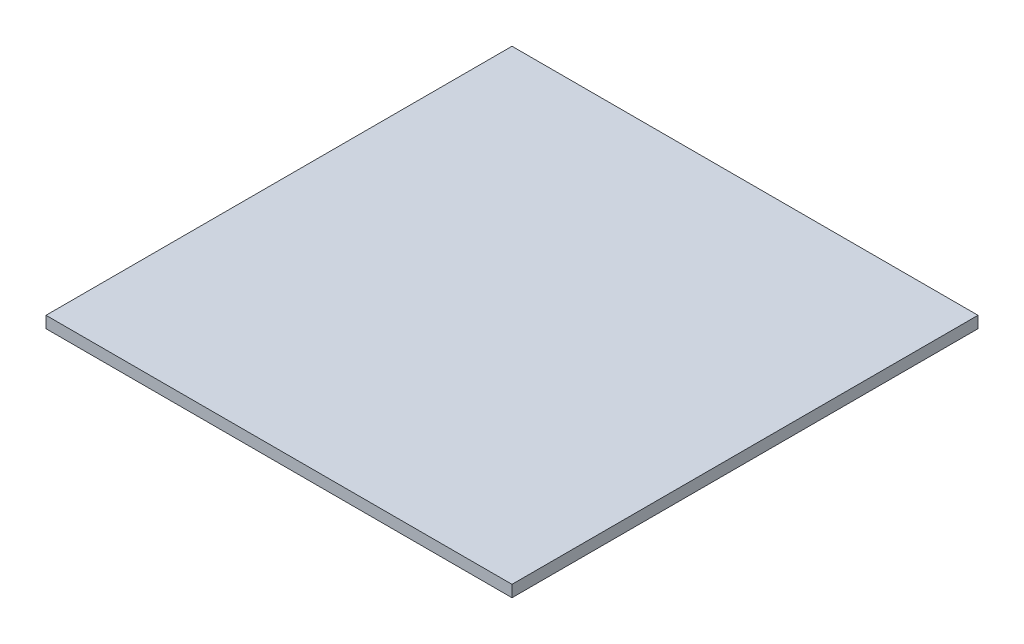
SolidWorks part; units mm, degrees
ref_plane "Front Plane" through (0, 0, 0) normal (0, 0, 1) x (1, 0, 0)
ref_plane "Top Plane" through (0, 0, 0) normal (0, 1, 0) x (1, 0, 0)
ref_plane "Right Plane" through (0, 0, 0) normal (1, 0, 0) x (0, 0, -1)
sketch "Sketch1" plane through (0, 0, 0) normal (0, 1, 0) x (1, 0, 0)
  line L1 (-4000, -4000) -> (4000, -4000)
  line L2 (-4000, -4000) -> (-4000, 4000)
  line L3 (-4000, 4000) -> (4000, 4000)
  line L4 (4000, -4000) -> (4000, 4000)
  line L5 (-4000, -4000) -> (4000, 4000) construction
  line L6 (-4000, 4000) -> (4000, -4000) construction
  point P0 (0, 0)
  dimension "D1" = 8000
  dimension "D2" = 8000
extrude "Boss-Extrude1" add sketch "Sketch1" along normal blind 200
